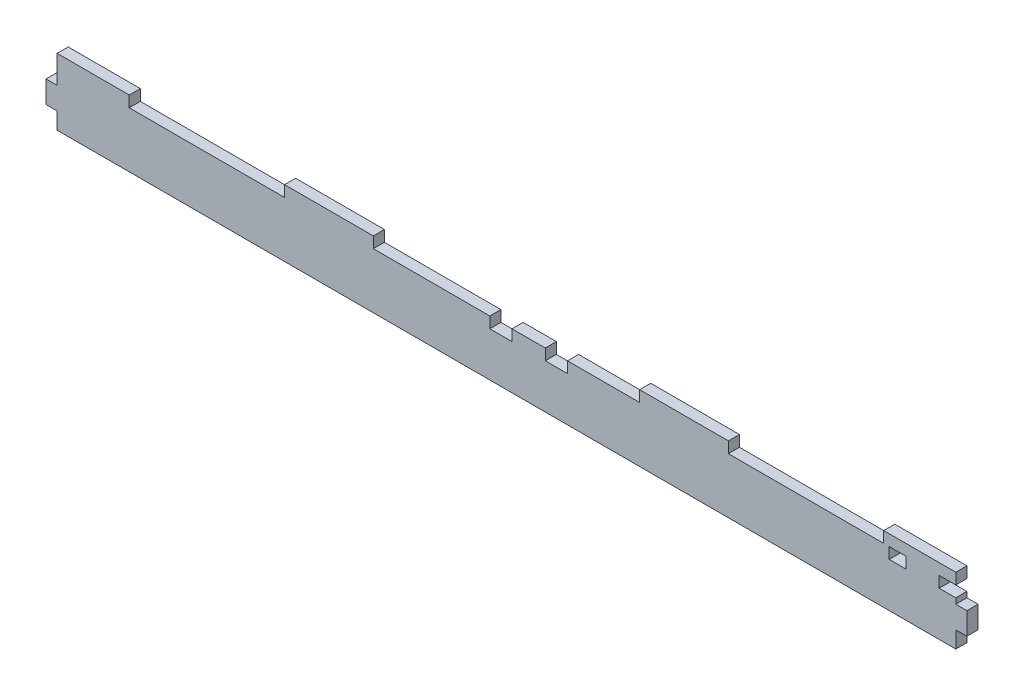
SolidWorks part; units mm, degrees
ref_plane "Front Plane" through (0, 0, 0) normal (0, 0, 1) x (1, 0, 0)
ref_plane "Top Plane" through (0, 0, 0) normal (0, 1, 0) x (1, 0, 0)
ref_plane "Right Plane" through (0, 0, 0) normal (1, 0, 0) x (0, 0, -1)
sketch "Sketch1" plane through (0, 0, 0) normal (0, 0, 1) x (1, 0, 0)
  line L0 (252.5, 195) -> (252.5, 170) construction
  line L1 (277.5, 254.5874) -> (277.5, 116.6829) construction
  line L8 (480, 177.5) -> (485, 177.5)
  line L9 (480, 170) -> (480, 177.5)
  line L11 (447.5, 195) -> (377.5, 195)
  line L12 (480, 190) -> (480, 187.5)
  line L13 (480, 187.5) -> (485, 187.5)
  line L14 (485, 187.5) -> (485, 177.5)
  line L15 (377.5, 200) -> (377.5, 195)
  line L16 (337.5, 200) -> (377.5, 200)
  line L17 (337.5, 195) -> (337.5, 200)
  line L18 (480, 200) -> (480, 195)
  line L19 (447.5, 200) -> (480, 200)
  line L20 (447.5, 195) -> (447.5, 200)
  line L21 (435, 192.1418) -> (435, 212.7842) construction
  line L22 (217.5, 195) -> (270, 195)
  line L25 (107.5, 195) -> (107.5, 200)
  line L26 (107.5, 200) -> (75, 200)
  line L27 (75, 200) -> (75, 195)
  line L29 (217.5, 195) -> (217.5, 200)
  line L30 (217.5, 200) -> (177.5, 200)
  line L31 (177.5, 200) -> (177.5, 195)
  line L40 (70, 187.5) -> (70, 177.5)
  line L43 (75, 187.5) -> (70, 187.5)
  line L48 (430, 182.5) -> (424.9156, 182.5) construction
  line L49 (75, 195) -> (75, 187.5)
  line L50 (107.5, 195) -> (177.5, 195)
  line L58 (75, 170) -> (75, 177.5)
  line L60 (75, 177.5) -> (70, 177.5)
  line L73 (480, 170) -> (75, 170)
  line L75 (450, 195) -> (457.5, 195)
  line L76 (450, 195) -> (450, 190)
  line L77 (450, 190) -> (457.5, 190)
  line L78 (457.5, 195) -> (457.5, 190)
  line L79 (472.5, 195) -> (480, 195)
  line L80 (472.5, 195) -> (472.5, 190)
  line L85 (472.5, 190) -> (480, 190)
  line L103 (295, 195) -> (295, 190)
  line L104 (295, 190) -> (305, 190)
  line L105 (305, 190) -> (305, 195)
  line L107 (270, 195) -> (270, 190)
  line L108 (270, 190) -> (280, 190)
  line L109 (280, 190) -> (280, 195)
  line L110 (305, 195) -> (337.5, 195)
  line L111 (280, 195) -> (295, 195)
  point P33 (70, 182.5)
  point P47 (485, 182.5)
  dimension "D1" = 25
extrude "Boss-Extrude1" add sketch "Sketch1" along normal blind 5
